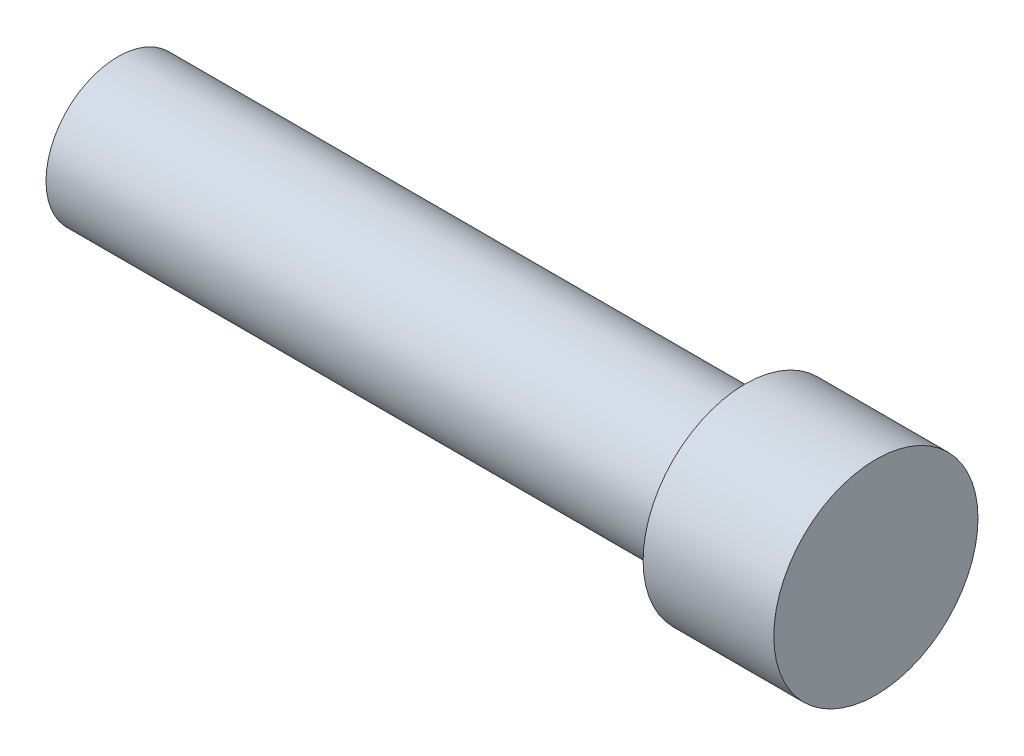
SolidWorks part; units mm, degrees
ref_plane "Front Plane" through (0, 0, 0) normal (0, 0, 1) x (1, 0, 0)
ref_plane "Top Plane" through (0, 0, 0) normal (0, 1, 0) x (1, 0, 0)
ref_plane "Right Plane" through (0, 0, 0) normal (1, 0, 0) x (0, 0, -1)
sketch "Sketch1" plane through (0, 0, 0) normal (1, 0, 0) x (0, 0, -1)
  circle A0 centre (0, 0) radius 5.9531
  dimension "D1" = 11.9062
extrude "Boss-Extrude1" add sketch "Sketch1" along normal blind 7.62
sketch "Sketch2" plane through (0, 0, 0) normal (-1, 0, 0) x (0, 0, 1)
  circle A0 centre (0, 0) radius 4.191
  dimension "D1" = 8.382
extrude "Boss-Extrude2" add sketch "Sketch2" along normal blind 36.576
